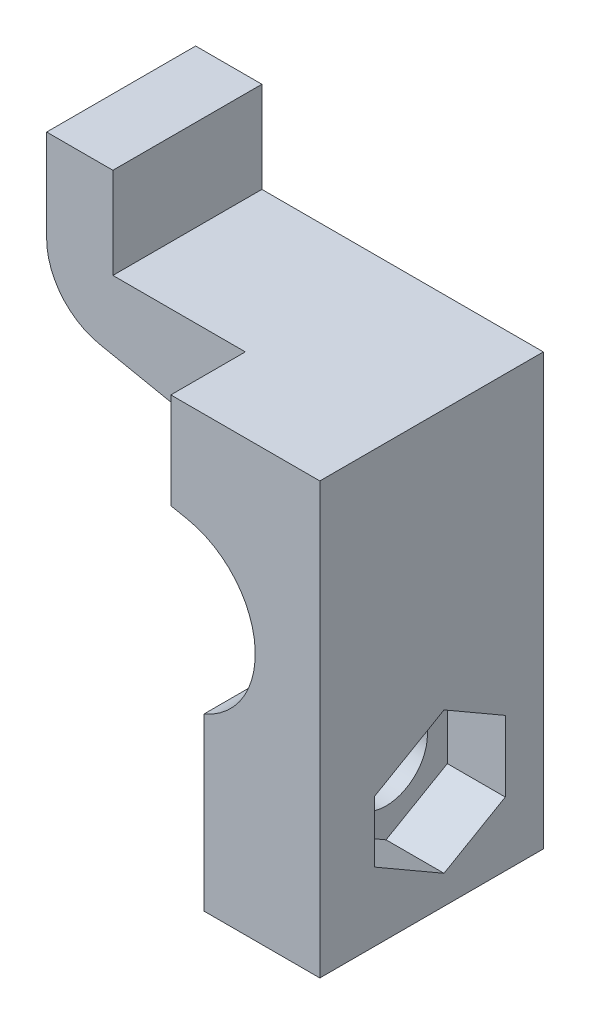
SolidWorks part; units mm, degrees
ref_plane "Front Plane" through (0, 0, 0) normal (0, 0, 1) x (1, 0, 0)
ref_plane "Top Plane" through (0, 0, 0) normal (0, 1, 0) x (1, 0, 0)
ref_plane "Right Plane" through (0, 0, 0) normal (1, 0, 0) x (0, 0, -1)
sketch "Sketch1" plane through (0, 0, 0) normal (0, 0, 1) x (1, 0, 0)
  line L0 (0, 0) -> (0, -5.5807)
  line L3 (14, -31.5) -> (21, -31.5)
  line L4 (21, -31.5) -> (21, -5.5)
  line L5 (21, -5.5) -> (4, -5.5)
  line L6 (4, -5.5) -> (4, 0)
  line L7 (4, 0) -> (0, 0)
  line L8 (14, -21.1915) -> (14, -31.5)
  line L9 (3.2005, -9.5) -> (13.0193, -11.5029)
  arc A0 (14, -21.1915) -> (13.0193, -11.5029) centre (12, -16.5) ccw
  arc A1 (0, -5.5807) -> (3.2005, -9.5) centre (4, -5.5807) ccw
  dimension "D2" = 10.2
  dimension "D10" = 4
  dimension "D1" = 8
  dimension "D3" = 11
  dimension "D4" = 4
  dimension "D5" = 4
  dimension "D6" = 2
  dimension "D7" = 15
  dimension "D8" = 7
  dimension "D9" = 5.5
extrude "Boss-Extrude1" add sketch "Sketch1" along normal blind 9
sketch "Sketch2" plane through (21, 0, 0) normal (1, 0, 0) x (0, 0, -1)
  line L0 (-9, -16.5) -> (0, -16.5) construction
  line L1 (0, -31.5) -> (0, -5.5) construction
  circle A0 centre (-6, -25.5) radius 2.5
  dimension "D2" = 5
  dimension "D1" = 9
  dimension "D3" = 6
extrude "Cut-Extrude1" cut sketch "Sketch2" against normal through all
sketch "Sketch3" plane through (0, 0, 9) normal (0, 0, 1) x (1, 0, 0)
  line L0 (12, -5.5) -> (12, -11.295)
  line L8 (4, 0) -> (0, 0)
  line L9 (0, 0) -> (0, -5.5807)
  line L10 (3.2005, -9.5) -> (13.0193, -11.5029)
  line L11 (14, -21.1915) -> (14, -31.5)
  line L12 (14, -31.5) -> (21, -31.5)
  line L13 (21, -31.5) -> (21, -5.5)
  line L14 (21, -5.5) -> (4, -5.5)
  line L15 (4, -5.5) -> (4, 0)
  line L18 (12, -11.295) -> (13.0193, -11.5029)
  line L19 (14, -21.1915) -> (14, -31.5)
  line L20 (14, -31.5) -> (21, -31.5)
  line L21 (21, -31.5) -> (21, -5.5)
  line L22 (21, -5.5) -> (12, -5.5)
  arc A2 (0, -5.5807) -> (3.2005, -9.5) centre (4, -5.5807) ccw
  arc A3 (14, -21.1915) -> (13.0193, -11.5029) centre (12, -16.5) ccw
  arc A5 (14, -21.1915) -> (13.0193, -11.5029) centre (12, -16.5) ccw
  dimension "D2" = 9
  dimension "D1" = 0
extrude "Boss-Extrude2" add sketch "Sketch3" along normal blind 4.5
sketch "Sketch4" plane through (21, 0, 0) normal (1, 0, 0) x (0, 0, -1)
  line L0 (-10.2, -23.6525) -> (-10.2, -27.3475)
  line L1 (-2.3, -23.3638) -> (-6, -21.2276)
  line L2 (-6, -21.2276) -> (-10.2, -23.6525)
  line L3 (-9.7, -21.8638) -> (-9.7, -26.1362) construction
  line L4 (-10.2, -27.3475) -> (-6, -29.7724)
  line L5 (-6, -29.7724) -> (-2.3, -27.6362)
  line L6 (-2.3, -27.6362) -> (-2.3, -23.3638)
  circle A0 centre (-6, -25.5) radius 3.7 construction
  dimension "D1" = 7.4
  dimension "D2" = 0.5
extrude "Cut-Extrude2" cut sketch "Sketch4" against normal blind 3.5
